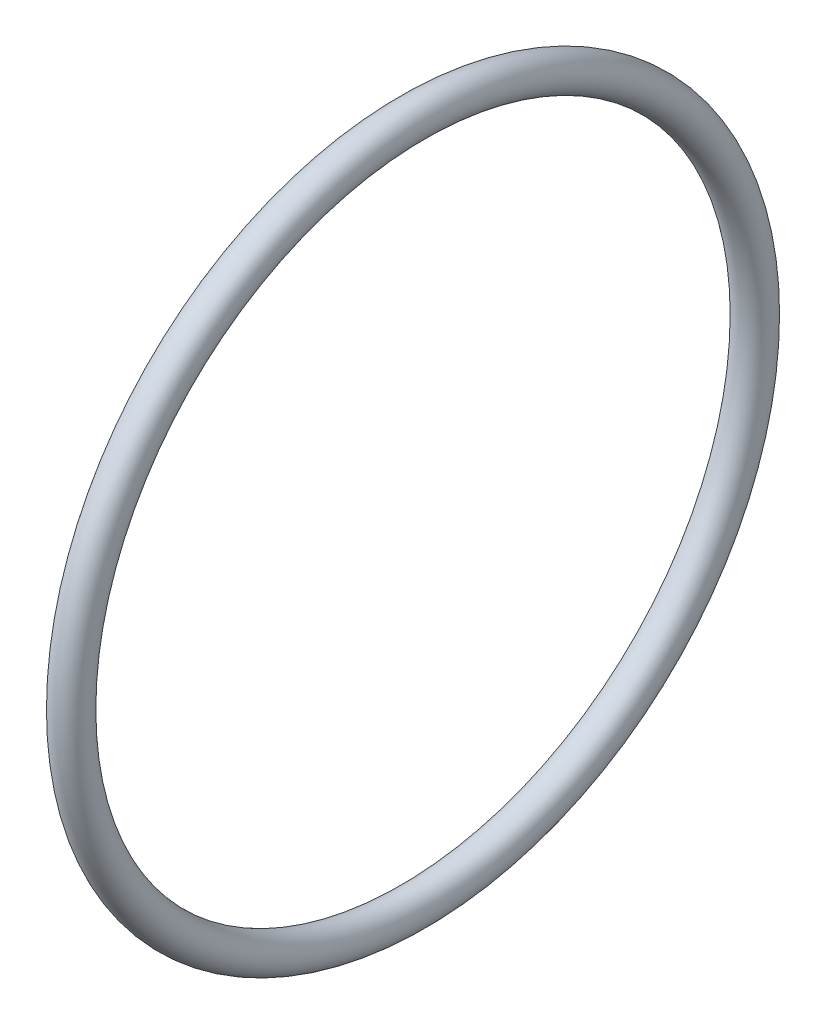
SolidWorks part; units mm, degrees
material "天然橡胶"
ref_plane "前视基准面" through (0, 0, 0) normal (0, 0, 1) x (1, 0, 0)
ref_plane "上视基准面" through (0, 0, 0) normal (0, 1, 0) x (1, 0, 0)
ref_plane "右视基准面" through (0, 0, 0) normal (1, 0, 0) x (0, 0, -1)
sketch "草图1" plane through (0, 0, 0) normal (0, 0, 1) x (1, 0, 0)
  line L0 (0, 0) -> (0, 18) construction
  line L1 (0, 0) -> (-8.3079, 0) construction
  circle A0 centre (0, 17.125) radius 0.875
  dimension "D1" = 18
  dimension "D2" = 1.75
revolve "旋转1" add sketch "草图1" angle 360 about L1
